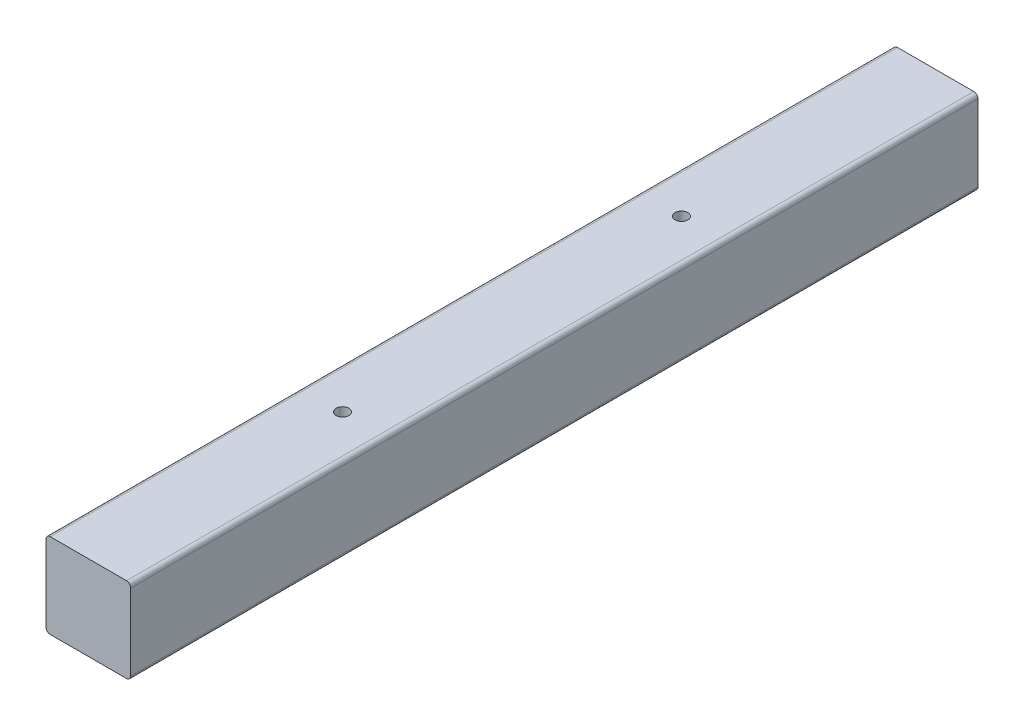
SolidWorks part; units mm, degrees
ref_plane "正面" through (0, 0, 0) normal (0, 0, 1) x (1, 0, 0)
ref_plane "平面" through (0, 0, 0) normal (0, 1, 0) x (1, 0, 0)
ref_plane "右側面" through (0, 0, 0) normal (1, 0, 0) x (0, 0, -1)
sketch "ｽｹｯﾁ1" plane through (0, 0, 0) normal (0, 0, 1) x (1, 0, 0)
  line L1 (-10, 10) -> (10, 10)
  line L2 (-10, 10) -> (-10, -10)
  line L3 (-10, -10) -> (10, -10)
  line L4 (10, 10) -> (10, -10)
  dimension "D1" = 20
  dimension "D2" = 20
  dimension "D3" = 10
  dimension "D4" = 10
extrude "ﾎﾞｽ - 押し出し1" add sketch "ｽｹｯﾁ1" along normal mid plane 200
fillet "ﾌｨﾚｯﾄ1" radius 1 4 edges at (-10, -10, 0) (10, -10, 0) (10, 10, 0) (-10, 10, 0)
sketch "ｽｹｯﾁ2" plane through (0, 10, 0) normal (0, 1, 0) x (1, 0, 0)
  circle A0 centre (0, 40) radius 1.5
  circle A1 centre (0, -40) radius 1.5
  dimension "D1" = 3
  dimension "D2" = 3
  dimension "D3" = 40
  dimension "D4" = 80
extrude "ｶｯﾄ - 押し出し1" cut sketch "ｽｹｯﾁ2" against normal up to next
